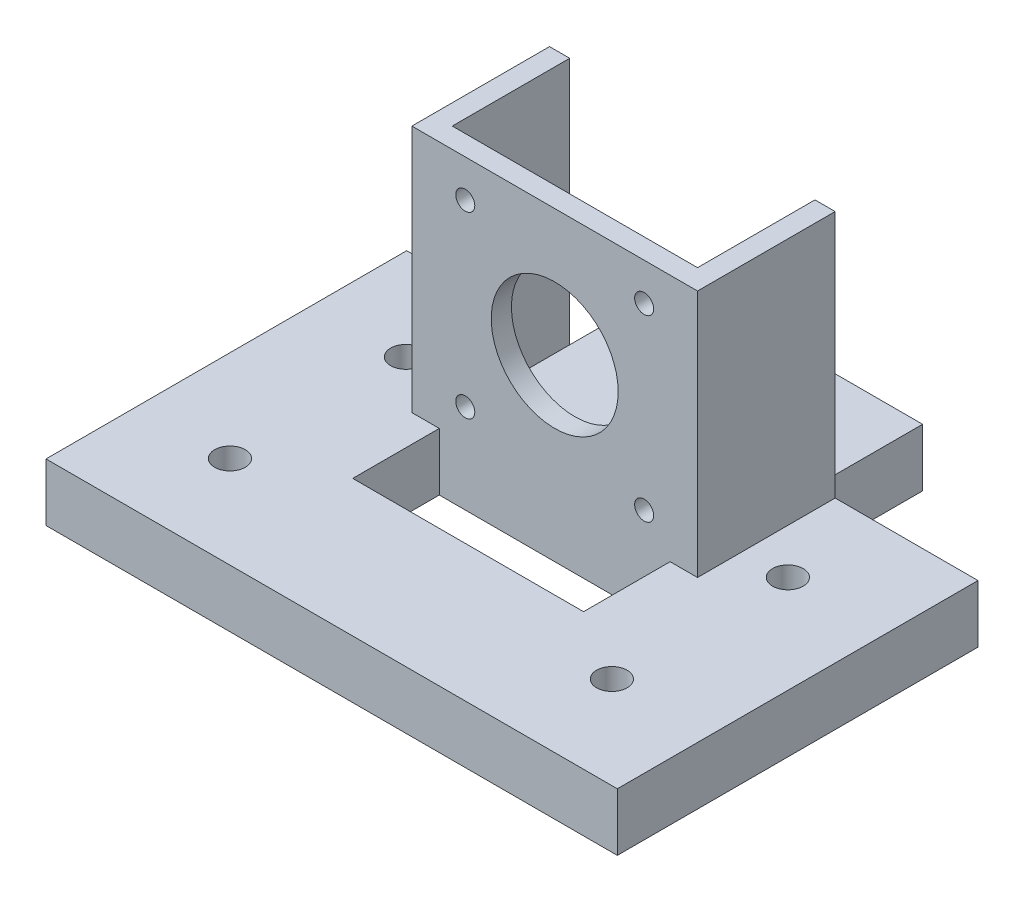
SolidWorks part; units mm, degrees
other "Markup1"
sketch "Sketch5" plane through (125, 53, 0) normal (0.0477, 0.9756, 0.2145) x (0.9988, -0.0483, -0.0024)
ref_plane "Front Plane" through (0, 0, 0) normal (0, 0, 1) x (1, 0, 0)
ref_plane "Top Plane" through (0, 0, 0) normal (0, 1, 0) x (1, 0, 0)
ref_plane "Right Plane" through (0, 0, 0) normal (1, 0, 0) x (0, 0, -1)
sketch "Sketch1" plane through (0, 0, 0) normal (0, 1, 0) x (1, 0, 0)
  line L10 (55.5, 38.65) -> (55.5, 23.65)
  line L11 (95.5, 38.65) -> (95.5, 23.65)
  line L14 (51, 85.65) -> (48, 85.65)
  line L17 (55.5, 23.65) -> (95.5, 23.65)
  line L21 (26, 62.5) -> (26, 0)
  line L22 (55.5, 38.65) -> (95.5, 38.65)
  line L23 (125, 62.5) -> (125, 0)
  line L26 (26, 0) -> (125, 0)
  line L28 (51, 85.65) -> (100, 85.65)
  line L30 (48, 85.65) -> (48, 62.5)
  line L31 (26, 62.5) -> (48, 62.5)
  line L32 (100, 85.65) -> (103, 85.65)
  line L33 (103, 85.65) -> (103, 62.5)
  line L34 (103, 62.5) -> (125, 62.5)
  circle A0 centre (108.0546, 46.5) radius 2.65
  circle A1 centre (41.8737, 46.5) radius 2.65
  circle A2 centre (41.8737, 16) radius 2.65
  circle A3 centre (108.0546, 16) radius 2.65
  dimension "D9" = 5.3
  dimension "D11" = 5.3
  dimension "D14" = 5.3
  dimension "D15" = 5.3
  dimension "D5" = 99
  dimension "D7" = 3
  dimension "D10" = 3
extrude "Boss-Extrude1" add sketch "Sketch1" along normal blind 10
sketch "Sketch8" plane through (0, 10, 0) normal (0, 1, 0) x (1, 0, 0)
  line L0 (54.25, 77.65) -> (54.25, 70.4887)
  line L3 (96.75, 77.65) -> (96.75, 70.4887)
  line L7 (48, 85.65) -> (48, 62.5) construction
  line L9 (103, 85.65) -> (103, 62.5) construction
  line L10 (48, 70.4887) -> (48, 85.65)
  line L11 (48, 85.65) -> (103, 85.65)
  line L12 (103, 85.65) -> (103, 70.4887)
  line L13 (48, 70.4887) -> (48, 62.5)
  line L15 (76, 77.65) -> (96.75, 77.65)
  line L16 (76, 77.65) -> (54.25, 77.65)
  line L17 (54.25, 62.5) -> (54.25, 70.4887)
  line L18 (48, 62.5) -> (54.25, 62.5)
  line L19 (48, 70.4887) -> (48, 62.5)
  line L20 (96.75, 70.4887) -> (96.75, 62.5)
  line L21 (103, 62.5) -> (103, 70.4887)
  line L22 (96.75, 62.5) -> (103, 62.5)
  line M8 (103, 62.5) -> (103, 85.65)
  line M9 (103, 85.65) -> (48, 85.65)
  line M10 (48, 85.65) -> (48, 62.5)
  dimension "D1" = 42.5
extrude "Cut-Extrude2" cut sketch "Sketch8" against normal blind 10 contours L20 L22 L18 L17 L0 L16 L15 L3 M8 M9 M10
sketch "Sketch12" plane through (0, 10, 0) normal (0, 1, 0) x (1, 0, 0)
  line L1 (54.25, 77.65) -> (96.75, 77.65)
  line L2 (54.25, 77.65) -> (54.25, 38.65)
  line L3 (54.25, 38.65) -> (96.75, 38.65)
  line L4 (96.75, 77.65) -> (96.75, 38.65)
  line L5 (54.25, 38.65) -> (96.75, 38.65)
  line L6 (54.25, 38.65) -> (54.25, 42.15)
  line L7 (54.25, 42.15) -> (96.75, 42.15)
  line L8 (96.75, 38.65) -> (96.75, 42.15)
  line M14 (55.5, 38.65) -> (95.5, 38.65)
  dimension "D1" = 39
  dimension "D2" = 42.5
  dimension "D3" = 3.5
extrude "Boss-Extrude3" add sketch "Sketch12" along normal blind 43 contours L7 L2 L3 L4 M14
sketch "Sketch13" plane through (0, 0, -38.65) normal (0, 0, 1) x (1, 0, 0)
  line L0 (26, 10) -> (125, 10) construction
  line L1 (54.25, 53) -> (54.25, 10) construction
  line L2 (54.25, 53) -> (96.75, 53) construction
  circle A0 centre (75.5, 31) radius 11
  circle A1 centre (60, 46.5) radius 1.65
  circle A2 centre (91, 46.5) radius 1.65
  circle A3 centre (91, 15.5) radius 1.65
  circle A4 centre (60, 15.5) radius 1.65
  dimension "D1" = 22
  dimension "D2" = 21.25
  dimension "D5" = 3.3
  dimension "D4" = 3.3
  dimension "D6" = 3.3
  dimension "D7" = 3.3
  dimension "D8" = 21
  dimension "D3" = 15.5
  dimension "D9" = 22
  dimension "D10" = 15.5
  dimension "D11" = 31
  dimension "D12" = 15.5
  dimension "D13" = 15.5
  dimension "D15" = 31
extrude "Cut-Extrude3" cut sketch "Sketch13" against normal up to next
sketch "Sketch15" plane through (0, 10, 0) normal (0, 1, 0) x (1, 0, 0)
  line L0 (96.75, 62.5) -> (125, 62.5) construction
  line L1 (96.75, 38.65) -> (100.25, 38.65)
  line L2 (96.75, 38.65) -> (96.75, 62.5)
  line L3 (96.75, 62.5) -> (100.25, 62.5)
  line L4 (100.25, 38.65) -> (100.25, 62.5)
  line L5 (26, 62.5) -> (54.25, 62.5) construction
  line L6 (54.25, 38.65) -> (50.75, 38.65)
  line L7 (54.25, 38.65) -> (54.25, 62.5)
  line L8 (54.25, 62.5) -> (50.75, 62.5)
  line L9 (50.75, 38.65) -> (50.75, 62.5)
  dimension "D1" = 3.5
  dimension "D2" = 3.5
extrude "Boss-Extrude4" add sketch "Sketch15" along normal blind 43
sketch "Sketch16" plane through (0, 10, 0) normal (0, 1, 0) x (1, 0, 0)
  line L1 (54.25, 77.65) -> (96.75, 77.65)
  line L2 (54.25, 77.65) -> (54.25, 81.15)
  line L3 (54.25, 81.15) -> (96.75, 81.15)
  line L4 (96.75, 77.65) -> (96.75, 81.15)
  dimension "D1" = 3.5
extrude "Boss-Extrude5" add sketch "Sketch16" against normal up to vertex (10 mm away)
sketch "Sketch17" plane through (0, 0, 0) normal (0, -1, 0) x (1, 0, 0)
  line L1 (26, 0) -> (125, 0)
  line L2 (26, 0) -> (26, -83.3159)
  line L3 (26, -83.3159) -> (125, -83.3159)
  line L4 (125, 0) -> (125, -83.3159)
